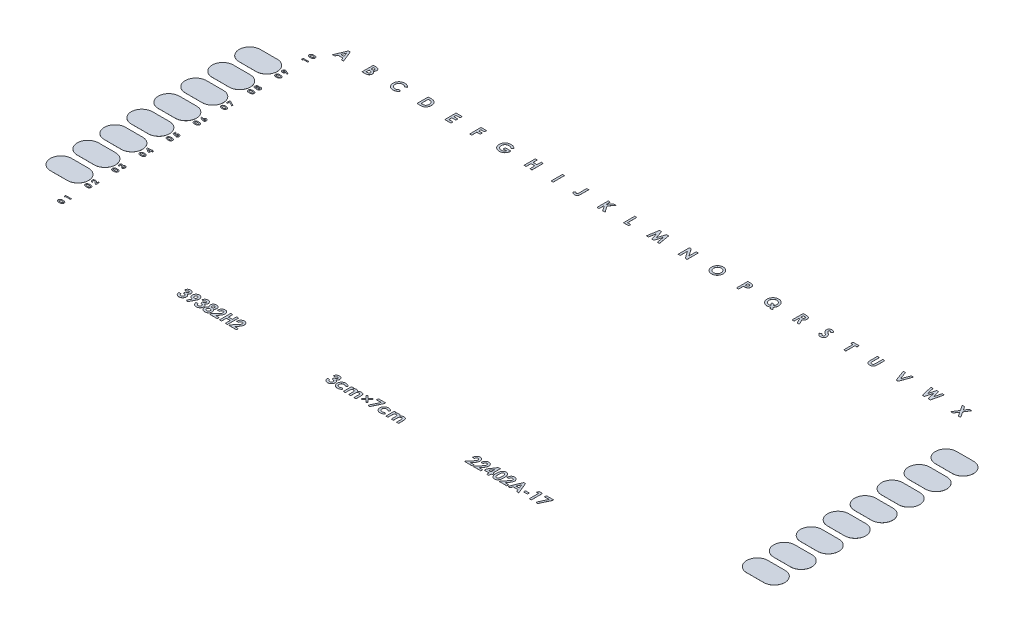
SolidWorks part; units mm, degrees
ref_plane "Front" through (0, 0, 0) normal (0, 0, 1) x (1, 0, 0)
ref_plane "Top" through (0, 0, 0) normal (0, 1, 0) x (1, 0, 0)
ref_plane "Right" through (0, 0, 0) normal (1, 0, 0) x (0, 0, -1)
sketch "Sketch1" plane through (0, 0, 0) normal (0, 1, 0) x (1, 0, 0)
  line L0 (0, 14.95) -> (0, 0) construction
  line L1 (0, 0) -> (-35, 0) construction
  line L2 (-35, 0) -> (-35, 1.27) construction
  line L3 (-35, 1.27) -> (-31, 1.27) construction
  line L4 (-33.6, 1.27) -> (-32, 1.27) construction
  line L5 (-33.6, 2.27) -> (-32, 2.27)
  line L6 (-33.6, 0.27) -> (-32, 0.27)
  line L7 (-33.6, 3.81) -> (-32, 3.81) construction
  line L8 (-33.6, 4.81) -> (-32, 4.81)
  line L9 (-33.6, 2.81) -> (-32, 2.81)
  line L10 (-33.6, 6.35) -> (-32, 6.35) construction
  line L11 (-33.6, 7.35) -> (-32, 7.35)
  line L12 (-33.6, 5.35) -> (-32, 5.35)
  line L13 (-33.6, 8.89) -> (-32, 8.89) construction
  line L14 (-33.6, 9.89) -> (-32, 9.89)
  line L15 (-33.6, 7.89) -> (-32, 7.89)
  line L16 (-33.6, -1.27) -> (-32, -1.27) construction
  line L17 (-33.6, -2.27) -> (-32, -2.27)
  line L18 (-33.6, -0.27) -> (-32, -0.27)
  line L19 (-33.6, -3.81) -> (-32, -3.81) construction
  line L20 (-33.6, -4.81) -> (-32, -4.81)
  line L21 (-33.6, -2.81) -> (-32, -2.81)
  line L22 (-33.6, -6.35) -> (-32, -6.35) construction
  line L23 (-33.6, -7.35) -> (-32, -7.35)
  line L24 (-33.6, -5.35) -> (-32, -5.35)
  line L25 (-33.6, -8.89) -> (-32, -8.89) construction
  line L26 (-33.6, -9.89) -> (-32, -9.89)
  line L27 (-33.6, -7.89) -> (-32, -7.89)
  line L28 (33.6, 1.27) -> (32, 1.27) construction
  line L29 (33.6, 2.27) -> (32, 2.27)
  line L30 (33.6, 0.27) -> (32, 0.27)
  line L31 (33.6, 3.81) -> (32, 3.81) construction
  line L32 (33.6, 4.81) -> (32, 4.81)
  line L33 (33.6, 2.81) -> (32, 2.81)
  line L34 (33.6, 6.35) -> (32, 6.35) construction
  line L35 (33.6, 7.35) -> (32, 7.35)
  line L36 (33.6, 5.35) -> (32, 5.35)
  line L37 (33.6, 8.89) -> (32, 8.89) construction
  line L38 (33.6, 9.89) -> (32, 9.89)
  line L39 (33.6, 7.89) -> (32, 7.89)
  line L40 (33.6, -1.27) -> (32, -1.27) construction
  line L41 (33.6, -2.27) -> (32, -2.27)
  line L42 (33.6, -0.27) -> (32, -0.27)
  line L43 (33.6, -3.81) -> (32, -3.81) construction
  line L44 (33.6, -4.81) -> (32, -4.81)
  line L45 (33.6, -2.81) -> (32, -2.81)
  line L46 (33.6, -6.35) -> (32, -6.35) construction
  line L47 (33.6, -7.35) -> (32, -7.35)
  line L48 (33.6, -5.35) -> (32, -5.35)
  line L49 (33.6, -8.89) -> (32, -8.89) construction
  line L50 (33.6, -9.89) -> (32, -9.89)
  line L51 (33.6, -7.89) -> (32, -7.89)
  arc A1 (-33.6, 2.27) -> (-33.6, 0.27) centre (-33.6, 1.27) ccw
  arc A2 (-32, 0.27) -> (-32, 2.27) centre (-32, 1.27) ccw
  arc A3 (-33.6, 4.81) -> (-33.6, 2.81) centre (-33.6, 3.81) ccw
  arc A4 (-32, 2.81) -> (-32, 4.81) centre (-32, 3.81) ccw
  arc A5 (-33.6, 7.35) -> (-33.6, 5.35) centre (-33.6, 6.35) ccw
  arc A6 (-32, 5.35) -> (-32, 7.35) centre (-32, 6.35) ccw
  arc A7 (-33.6, 9.89) -> (-33.6, 7.89) centre (-33.6, 8.89) ccw
  arc A8 (-32, 7.89) -> (-32, 9.89) centre (-32, 8.89) ccw
  arc A9 (-33.6, -2.27) -> (-33.6, -0.27) centre (-33.6, -1.27) cw
  arc A10 (-32, -0.27) -> (-32, -2.27) centre (-32, -1.27) cw
  arc A11 (-33.6, -4.81) -> (-33.6, -2.81) centre (-33.6, -3.81) cw
  arc A12 (-32, -2.81) -> (-32, -4.81) centre (-32, -3.81) cw
  arc A13 (-33.6, -7.35) -> (-33.6, -5.35) centre (-33.6, -6.35) cw
  arc A14 (-32, -5.35) -> (-32, -7.35) centre (-32, -6.35) cw
  arc A15 (-33.6, -9.89) -> (-33.6, -7.89) centre (-33.6, -8.89) cw
  arc A16 (-32, -7.89) -> (-32, -9.89) centre (-32, -8.89) cw
  arc A17 (33.6, 2.27) -> (33.6, 0.27) centre (33.6, 1.27) cw
  arc A18 (32, 0.27) -> (32, 2.27) centre (32, 1.27) cw
  arc A19 (33.6, 4.81) -> (33.6, 2.81) centre (33.6, 3.81) cw
  arc A20 (32, 2.81) -> (32, 4.81) centre (32, 3.81) cw
  arc A21 (33.6, 7.35) -> (33.6, 5.35) centre (33.6, 6.35) cw
  arc A22 (32, 5.35) -> (32, 7.35) centre (32, 6.35) cw
  arc A23 (33.6, 9.89) -> (33.6, 7.89) centre (33.6, 8.89) cw
  arc A24 (32, 7.89) -> (32, 9.89) centre (32, 8.89) cw
  arc A25 (33.6, -2.27) -> (33.6, -0.27) centre (33.6, -1.27) ccw
  arc A26 (32, -0.27) -> (32, -2.27) centre (32, -1.27) ccw
  arc A27 (33.6, -4.81) -> (33.6, -2.81) centre (33.6, -3.81) ccw
  arc A28 (32, -2.81) -> (32, -4.81) centre (32, -3.81) ccw
  arc A29 (33.6, -7.35) -> (33.6, -5.35) centre (33.6, -6.35) ccw
  arc A30 (32, -5.35) -> (32, -7.35) centre (32, -6.35) ccw
  arc A31 (33.6, -9.89) -> (33.6, -7.89) centre (33.6, -8.89) ccw
  arc A32 (32, -7.89) -> (32, -9.89) centre (32, -8.89) ccw
  point P9 (-32.8, 1.27)
  point P17 (-32.8, 3.81)
  point P24 (-32.8, 6.35)
  point P31 (-32.8, 8.89)
  point P37 (-32.8, -1.27)
  point P44 (-32.8, -3.81)
  point P51 (-32.8, -6.35)
  point P58 (-32.8, -8.89)
  point P65 (32.8, 1.27)
  point P72 (32.8, 3.81)
  point P79 (32.8, 6.35)
  point P86 (32.8, 8.89)
  point P93 (32.8, -1.27)
  point P100 (32.8, -3.81)
  point P107 (32.8, -6.35)
  point P114 (32.8, -8.89)
  dimension "D1" = 4
extrude "Boss-Extrude1" add sketch "Sketch1" along normal blind 0.005
sketch "Sketch2" plane through (0, 0, 0) normal (0, 1, 0) x (1, 0, 0)
  text T0 "<b>A B C D E F G H I J K L M N O P Q R S T U V W X</b>" font "Century Gothic" height in points 4
  point P1 (-29.7819, 12.8633)
extrude "Boss-Extrude2" add sketch "Sketch2" along normal up to surface (0.005 mm away) separate body up to face at (-32.8, 0.005, -8.89)
sketch "Sketch3" plane through (0, 0, 0) normal (0, 1, 0) x (1, 0, 0)
  line L0 (-30.3236, -12.0949) -> (-30.3236, 18.2542) construction
  text T0 "<b>01   02   03   04   05   06   07   08   09   10</b>" font "Century Gothic" height in points 2
  point P2 (-30.4839, 18.2542)
  point P4 (-30.2, -12.1505)
  point P5 (-30.3481, -11.43)
  point P6 (-30.2765, -12.0949)
extrude "Boss-Extrude3" add sketch "Sketch3" along normal up to surface (0.005 mm away) separate body up to face at (-32.8, 0.005, -8.89)
sketch "Sketch4" plane through (0, 0, 0) normal (0, 1, 0) x (1, 0, 0)
  text T0 "<b>39382H2                    3cm×7cm               22402A-17</b>" font "Century Gothic" height in points 4
extrude "Boss-Extrude4" add sketch "Sketch4" along normal up to surface (0.005 mm away) separate body up to face at (-32.8, 0.005, -8.89)
